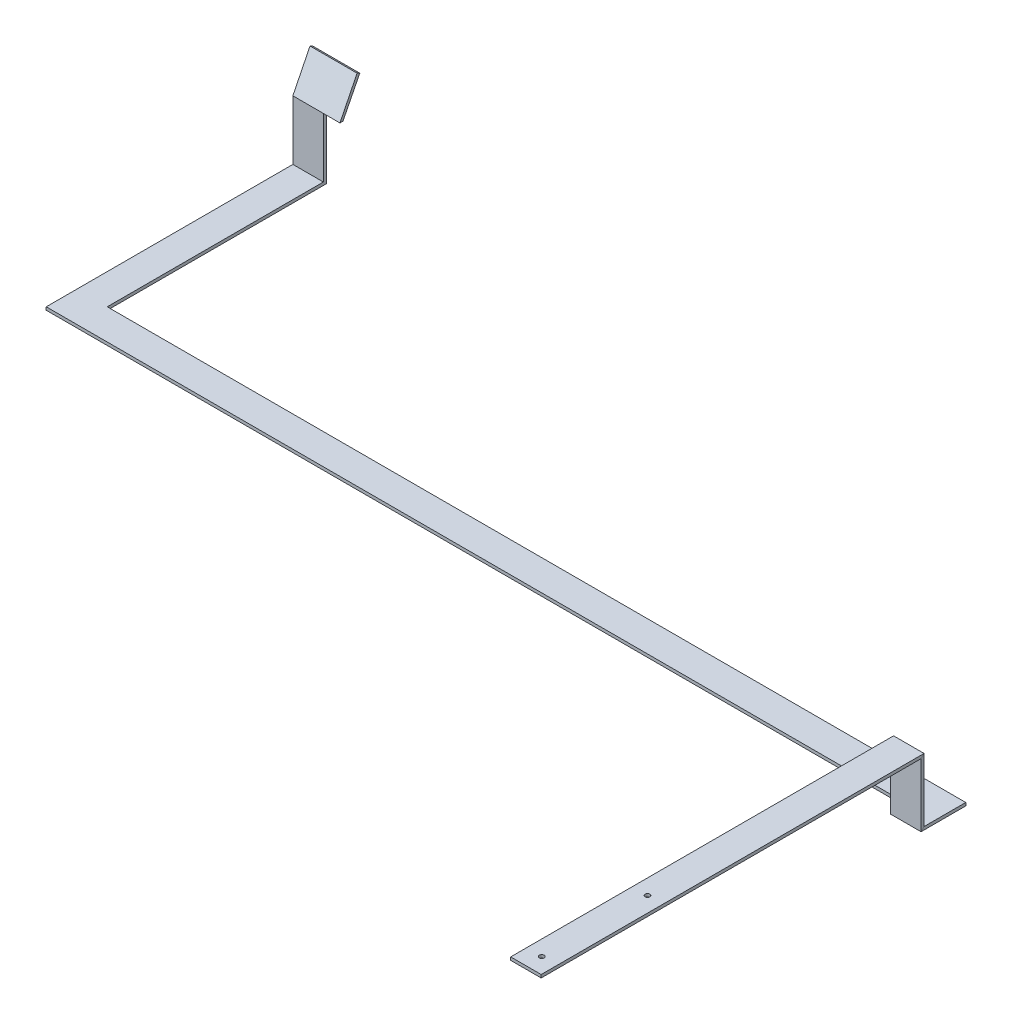
SolidWorks part; units mm, degrees
ref_plane "Alzado" through (0, 0, 0) normal (0, 0, 1) x (1, 0, 0)
ref_plane "Planta" through (0, 0, 0) normal (0, 1, 0) x (1, 0, 0)
ref_plane "Vista lateral" through (0, 0, 0) normal (1, 0, 0) x (0, 0, -1)
sketch "Croquis2" plane through (0, 0, 0) normal (0, 0, 1) x (1, 0, 0)
  line L1 (-31.75, 65) -> (31.75, 65)
  line L2 (-31.75, 65) -> (-31.75, -65)
  line L3 (-31.75, -65) -> (31.75, -65)
  line L4 (31.75, 65) -> (31.75, -65)
  line L5 (-31.75, 65) -> (31.75, -65) construction
  line L6 (-31.75, -65) -> (31.75, 65) construction
  point P0 (0, 0)
  dimension "D1" = 130
  dimension "D2" = 63.5
extrude "Saliente-Extruir1" add sketch "Croquis2" along normal blind 6.31
sketch "Croquis3" plane through (0, 0, 6.31) normal (0, 0, 1) x (1, 0, 0)
  line L1 (-31.75, -58.69) -> (31.75, -58.69)
  line L2 (-31.75, -58.69) -> (-31.75, -65)
  line L3 (-31.75, -65) -> (31.75, -65)
  line L4 (31.75, -58.69) -> (31.75, -65)
  line L5 (-31.75, -58.69) -> (31.75, -65) construction
  line L6 (-31.75, -65) -> (31.75, -58.69) construction
  point P0 (0, -61.845)
  dimension "D1" = 6.31
  dimension "D2" = 63.5
extrude "Saliente-Extruir2" add sketch "Croquis3" along normal blind 513.44
sketch "Croquis4" plane through (31.75, 0, 0) normal (1, 0, 0) x (0, 0, -1)
  line L1 (-456.25, -65) -> (-519.75, -65)
  line L2 (-456.25, -65) -> (-456.25, -58.69)
  line L3 (-456.25, -58.69) -> (-519.75, -58.69)
  line L4 (-519.75, -65) -> (-519.75, -58.69)
  line L5 (-456.25, -65) -> (-519.75, -58.69) construction
  line L6 (-456.25, -58.69) -> (-519.75, -65) construction
  point P0 (-488, -61.845)
  dimension "D1" = 63.5
extrude "Saliente-Extruir3" add sketch "Croquis4" along normal blind 1787.3
sketch "Croquis9" plane through (0, 0, 519.75) normal (0, 0, 1) x (1, 0, 0)
  line L0 (1819.05, -58.69) -> (-31.75, -58.69) construction
  line L1 (1755.55, -58.69) -> (1819.05, -58.69)
  line L2 (1755.55, -58.69) -> (1755.55, -65)
  line L3 (1755.55, -65) -> (1819.05, -65)
  line L4 (1819.05, -58.69) -> (1819.05, -65)
  line L5 (1755.55, -58.69) -> (1819.05, -65) construction
  line L6 (1755.55, -65) -> (1819.05, -58.69) construction
  point P0 (1787.3, -61.845)
  dimension "D1" = 63.5
sketch3d "Croquis3D3"
  line L0 (1787.3, -61.845, 519.75) -> (1787.3, -61.845, 546.16)
  line L1 (1787.3, -61.845, 546.16) -> (1787.3, 69.915, 546.16)
  line L2 (1787.3, 69.915, 546.16) -> (1787.3, 69.915, 1340.16)
  dimension "D1" = 26.41
  dimension "D2" = 131.76
  dimension "D3" = 794
sweep "Barrer2" add profiles "Croquis9" path "Croquis3D3"
sketch "Croquis11" plane through (-31.75, 0, 0) normal (-1, 0, 0) x (0, 0, 1)
  line L0 (0, 65) -> (-35.0062, 134.0808)
  line L1 (-35.0062, 134.0808) -> (-29.3776, 136.933)
  line L2 (-29.3776, 136.933) -> (6.31, 65)
  line L3 (0, 65) -> (6.31, 65)
  dimension "D1" = 6.31
extrude "Saliente-Extruir4" add sketch "Croquis11" against normal blind 98
sketch "Croquis12" plane through (0, 73.07, 0) normal (0, 1, 0) x (1, 0, 0)
  line L0 (1787.3, -1340.16) -> (1787.3, -1307.16) construction
  line L1 (1787.3, -546.16) -> (1787.3, -1340.16) construction
  line L2 (1787.3, -1307.16) -> (1787.3, -1087.16) construction
  circle A0 centre (1787.3, -1307.16) radius 5
  circle A1 centre (1787.3, -1087.16) radius 5
  dimension "D3" = 10
  dimension "D4" = 10
  dimension "D1" = 33
  dimension "D2" = 220
extrude "Cortar-Extruir1" cut sketch "Croquis12" against normal blind 10
